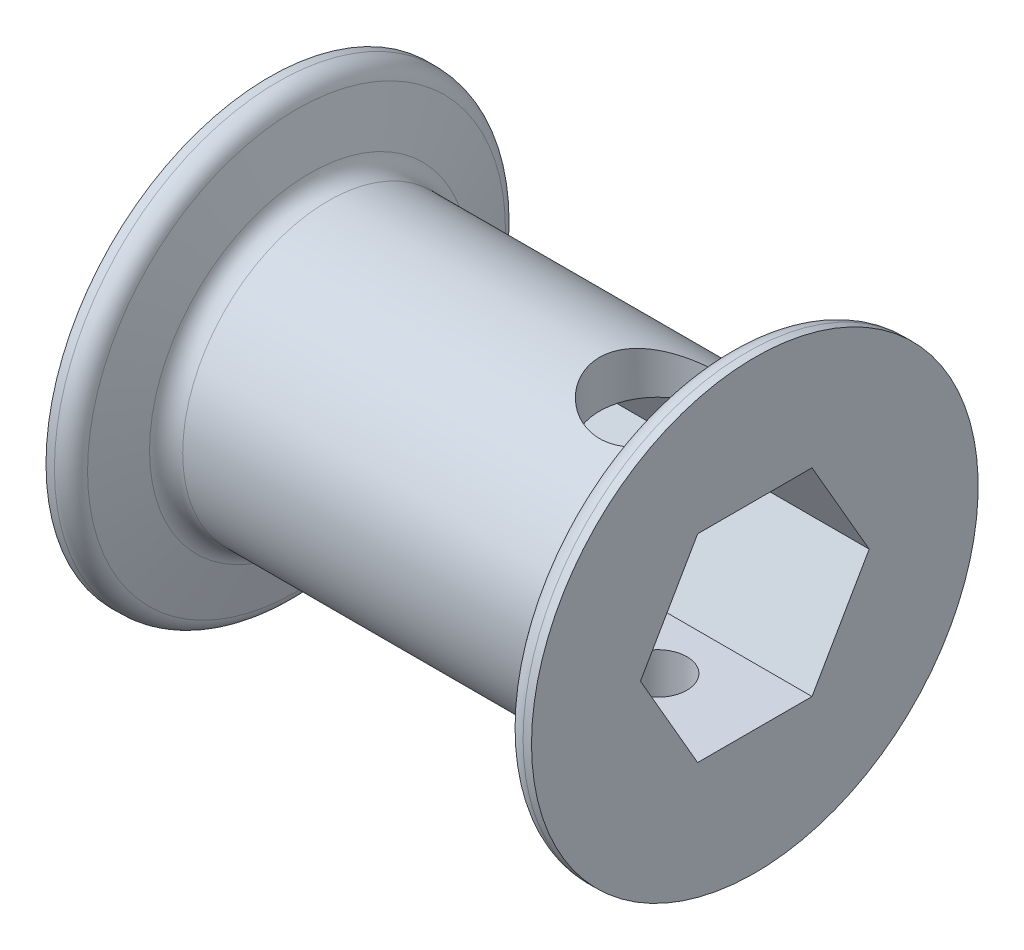
SolidWorks part; units mm, degrees
ref_plane "Front Plane" through (0, 0, 0) normal (0, 0, 1) x (1, 0, 0)
ref_plane "Top Plane" through (0, 0, 0) normal (0, 1, 0) x (1, 0, 0)
ref_plane "Right Plane" through (0, 0, 0) normal (1, 0, 0) x (0, 0, -1)
sketch "Sketch1" plane through (0, 0, 0) normal (0, 0, 1) x (1, 0, 0)
  line L0 (0, 0) -> (31.75, 0)
  line L1 (31.75, 0) -> (31.75, 14.605)
  line L2 (31.75, 14.605) -> (30.226, 14.605)
  line L3 (30.226, 14.605) -> (28.8648, 9.525)
  line L4 (28.8648, 9.525) -> (2.8852, 9.525)
  line L5 (2.8852, 9.525) -> (1.524, 14.605)
  line L6 (1.524, 14.605) -> (0, 14.605)
  line L7 (0, 14.605) -> (0, 0)
  line L8 (31.75, 0) -> (36.7691, 0) construction
  dimension "D1" = 31.75
  dimension "D2" = 5.08
  dimension "D3" = 5.08
  dimension "D4" = 19.05
  dimension "D5" = 15
  dimension "D6" = 1.524
revolve "Revolve1" add sketch "Sketch1" angle 360 about L8
sketch "Sketch2" plane through (0, 0, 0) normal (-1, 0, 0) x (0, 0, 1)
  line L0 (-14.605, 0) -> (14.605, 0) construction
  line L1 (7.479, 0) -> (3.7395, 6.477)
  line L2 (3.7395, 6.477) -> (-3.7395, 6.477)
  line L3 (-3.7395, 6.477) -> (-7.479, 0)
  line L4 (-7.479, 0) -> (-3.7395, -6.477)
  line L5 (-3.7395, -6.477) -> (3.7395, -6.477)
  line L6 (3.7395, -6.477) -> (7.479, 0)
  circle A0 centre (0, 0) radius 6.477 construction
  circle A2 centre (0, 0) radius 14.605 construction
  dimension "D1" = 12.954
  dimension "D2" = 7.126
extrude "Cut-Extrude1" cut sketch "Sketch2" against normal through all
fillet "Fillet1" radius 1.27 4 edges at (2.8852, 0, 9.525) (1.524, 0, 14.605) (30.226, 0, 14.605) (28.8648, 0, 9.525)
sketch "Sketch3" plane through (0, 0, 0) normal (0, 0, 1) x (1, 0, 0)
  line L6 (31.75, -14.605) -> (31.75, 14.605) construction
  line L12 (0, 0) -> (31.817, 0) construction
  line L13 (31.75, 14.605) -> (31.2005, 14.605) construction
  line L14 (31.2005, -14.605) -> (31.75, -14.605) construction
  line L15 (27.305, -14.605) -> (25.4, -14.605)
  line L16 (27.305, -14.605) -> (27.305, -0.0253)
  line L17 (25.4, -14.605) -> (25.4, 14.605)
  line L18 (29.21, -0.0253) -> (27.305, -0.0253)
  line L19 (25.4, 14.605) -> (25.4, 15.4744) construction
  line L20 (25.4, 14.605) -> (29.21, 14.605)
  line L21 (29.21, 14.605) -> (29.21, -0.0253)
  dimension "D1" = 7.62
  dimension "D2" = 3.81
  dimension "D3" = 6.35
  dimension "D4" = 0.0506
revolve "Cut-Revolve1" cut sketch "Sketch3" angle 360 about L19
